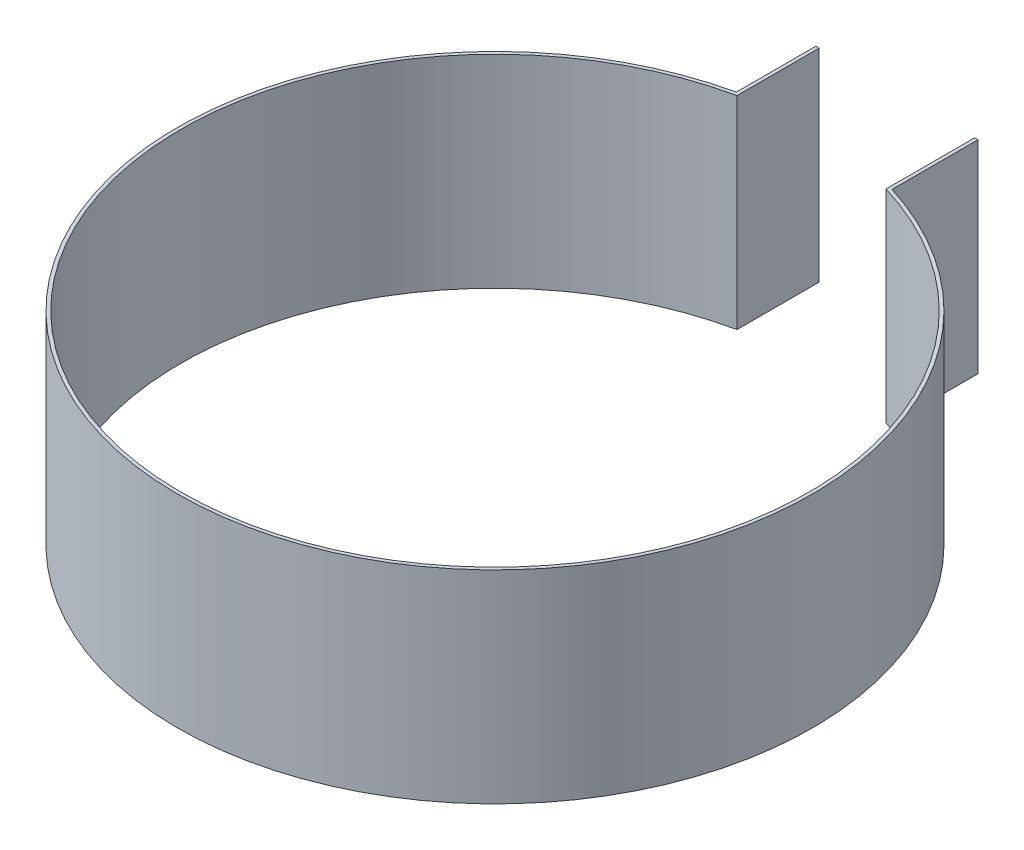
SolidWorks part; units mm, degrees
ref_plane "Front Plane" through (0, 0, 0) normal (0, 0, 1) x (1, 0, 0)
ref_plane "Top Plane" through (0, 0, 0) normal (0, 1, 0) x (1, 0, 0)
ref_plane "Right Plane" through (0, 0, 0) normal (1, 0, 0) x (0, 0, -1)
sketch "Sketch1" plane through (0, 0, 0) normal (0, 1, 0) x (1, 0, 0)
  circle A0 centre (0, 0) radius 47
  dimension "D1" = 94
extrude "Boss-Extrude1" add sketch "Sketch1" along normal blind 30
sketch "Sketch3" plane through (0, 30, 0) normal (0, 1, 0) x (1, 0, 0)
  line L0 (-10.1622, 42.6622) -> (13.8378, 42.6622)
  line L1 (13.8378, 42.6622) -> (13.8378, 57.6622)
  line L2 (13.8378, 57.6622) -> (-10.1622, 57.6622)
  line L3 (-10.1622, 57.6622) -> (-10.1622, 42.6622)
extrude "Boss-Extrude2" add sketch "Sketch3" along normal mid plane 60
sketch "Sketch4" plane through (0, 60, 0) normal (0, 1, 0) x (1, 0, 0)
  line L0 (-10.1622, 57.6622) -> (-10.1622, 42.6622)
  line L1 (-10.1622, 42.6622) -> (13.8378, 42.6622)
  line L2 (13.8378, 42.6622) -> (13.8378, 57.6622)
  line L3 (13.8378, 57.6622) -> (-10.1622, 57.6622)
extrude "Cut-Extrude1" cut sketch "Sketch4" against normal blind 30
sketch "Sketch5" plane through (0, 30, 0) normal (0, 1, 0) x (1, 0, 0)
  line L0 (-9.6622, 57.6622) -> (-9.6622, 45.6622)
  line L1 (13.8378, 57.6622) -> (-10.1622, 57.6622) construction
  line L2 (-9.6622, 45.6622) -> (13.3378, 45.6622)
  line L3 (13.3378, 45.6622) -> (13.3378, 57.6622)
  line L4 (13.3378, 57.6622) -> (-9.0364, 57.6622)
  line L5 (-10.1622, 57.6622) -> (-10.1622, 45.8882) construction
  line L6 (13.8378, 44.9167) -> (13.8378, 57.6622) construction
  point P9 (13.3378, 51.6622)
  dimension "D1" = 12
  dimension "D2" = 0.5
  dimension "D3" = 0.5
extrude "Cut-Extrude2" cut sketch "Sketch5" against normal blind 30 and the other way through all
sketch "Sketch6" plane through (0, 30, 0) normal (0, 1, 0) x (1, 0, 0)
  circle A0 centre (0, 0) radius 46.5
  dimension "D1" = 93
extrude "Cut-Extrude3" cut sketch "Sketch6" against normal blind 30
ref_plane "Plane1" through (13.3378, 30, -45.6622) normal (1, 0, 0) x (0, 0, -1)
sketch "Sketch9" plane through (0, 0, -45.6622) normal (0, 0, -1) x (-1, 0, 0)
  line L0 (-13.3378, 30) -> (-8.7871, 30)
  line L1 (-13.3378, 31.2515) -> (-13.3378, 28.7485) construction
  line L2 (-8.7871, 30) -> (-13.3378, 30) construction
  line L3 (-8.7871, 30) -> (-8.7871, 0)
  line L4 (-8.7871, 0) -> (-13.3378, 0)
  line L5 (-13.3378, 0) -> (-13.3378, 30)
extrude "Cut-Extrude4" cut sketch "Sketch9" against normal blind 30
sketch "Sketch10" plane through (0, 0, -45.6622) normal (0, 0, -1) x (-1, 0, 0)
  line L0 (8.7871, 30) -> (9.6622, 30)
  line L1 (9.6622, 30) -> (9.6622, 0)
  line L2 (9.6622, 0) -> (8.7871, 0)
  line L3 (8.7871, 0) -> (8.7871, 30)
extrude "Cut-Extrude5" cut sketch "Sketch10" against normal blind 30
